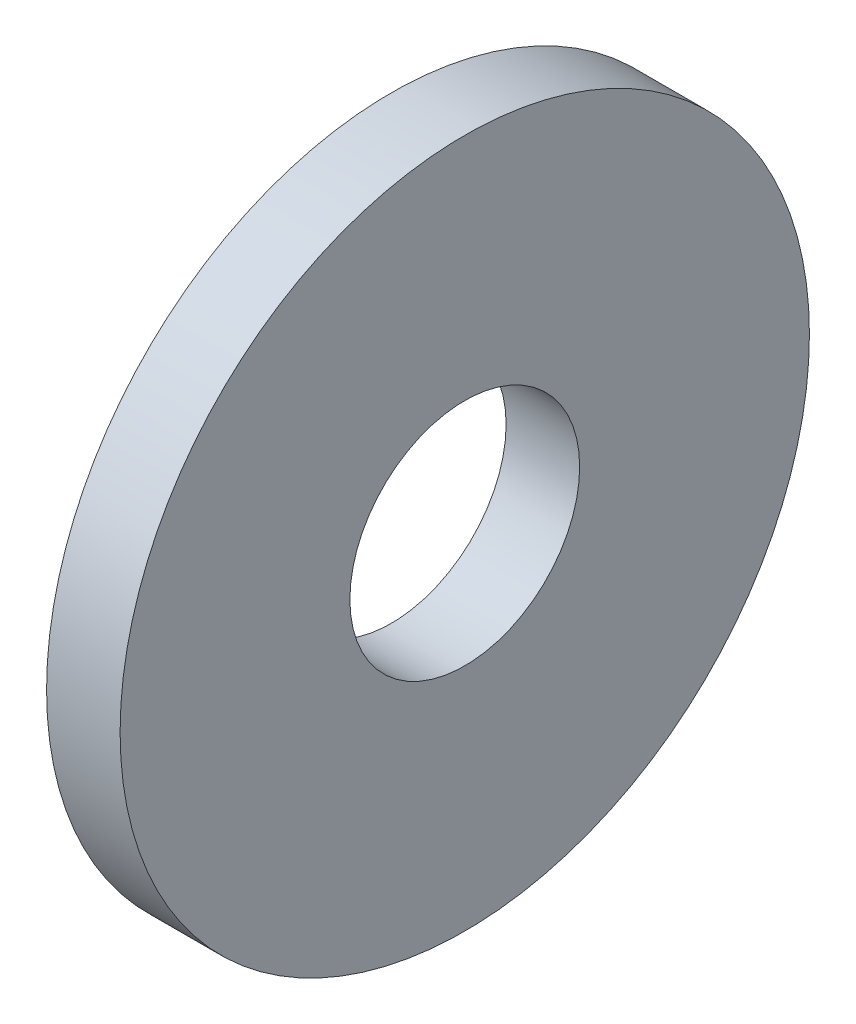
SolidWorks part; units mm, degrees
material "Nylon 6/10"
ref_plane "Plane1" through (0, 0, 0) normal (0, 0, 1) x (1, 0, 0)
ref_plane "Plane2" through (0, 0, 0) normal (0, 1, 0) x (1, 0, 0)
ref_plane "Plane3" through (0, 0, 0) normal (1, 0, 0) x (0, 0, -1)
revolve "Base-Revolve" add sketch "Sketch1" angle 360 about L0
sketch "Sketch1" plane through (0, 0, 0) normal (0, 0, 1) x (1, 0, 0)
  line L0 (-34.925, 0) -> (9.525, 0) construction
  line L1 (0, 1.5875) -> (0, 4.7625)
  line L2 (0, 4.7625) -> (-1.016, 4.7625)
  line L3 (-1.016, 4.7625) -> (-1.016, 1.5875)
  line L4 (-1.016, 1.5875) -> (0, 1.5875)
  dimension "Thickness" = 1.016
  dimension "Inside_dia" = 3.175
  dimension "Outside_dia" = 9.525
